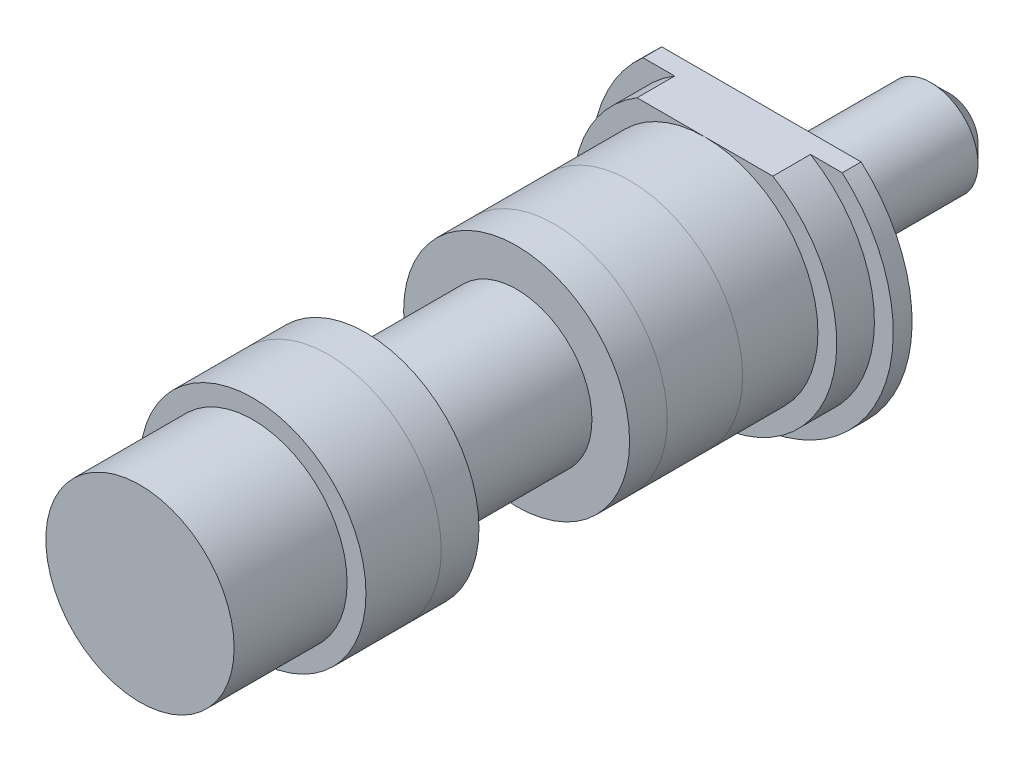
SolidWorks part; units mm, degrees
material "Stainless Steel (ferritic)"
ref_plane "Front" through (0, 0, 0) normal (0, 0, 1) x (1, 0, 0)
ref_plane "Top" through (0, 0, 0) normal (0, 1, 0) x (1, 0, 0)
ref_plane "Right" through (0, 0, 0) normal (1, 0, 0) x (0, 0, -1)
sketch "Sketch1" plane through (0, 0, 0) normal (0, 0, 1) x (1, 0, 0)
  circle A0 centre (0, 0) radius 4
  dimension "D1" = 8
extrude "Boss-Extrude1" add sketch "Sketch1" along normal blind 0.5
sketch "Sketch2" plane through (0, 0, 0.5) normal (0, 0, 1) x (1, 0, 0)
  circle A0 centre (0, 0) radius 3.5
extrude "Boss-Extrude2" add sketch "Sketch2" along normal blind 1
sketch "Sketch3" plane through (0, 0, 1.5) normal (0, 0, 1) x (1, 0, 0)
  circle A0 centre (0, 0) radius 3
extrude "Boss-Extrude3" add sketch "Sketch3" along normal blind 2
sketch "Sketch4" plane through (0, 0, 3.5) normal (0, 0, 1) x (1, 0, 0)
  circle A0 centre (0, 0) radius 2
extrude "Boss-Extrude4" add sketch "Sketch4" along normal blind 2
sketch "Sketch5" plane through (0, 0, 5.5) normal (0, 0, 1) x (1, 0, 0)
  circle A0 centre (0, 0) radius 3
extrude "Boss-Extrude5" add sketch "Sketch5" along normal blind 1
sketch "Sketch6" plane through (0, 0, 6.5) normal (0, 0, 1) x (1, 0, 0)
  circle A0 centre (0, 0) radius 2
extrude "Boss-Extrude6" add sketch "Sketch6" along normal blind 4
sketch "Sketch7" plane through (0, 0, 10.5) normal (0, 0, 1) x (1, 0, 0)
  circle A0 centre (0, 0) radius 3
extrude "Boss-Extrude7" add sketch "Sketch7" along normal blind 1
sketch "Sketch8" plane through (0, 0, 11.5) normal (0, 0, 1) x (1, 0, 0)
  circle A0 centre (0, 0) radius 2
extrude "Boss-Extrude8" add sketch "Sketch8" along normal blind 2
sketch "Sketch9" plane through (0, 0, 13.5) normal (0, 0, 1) x (1, 0, 0)
  circle A0 centre (0, 0) radius 2.5
extrude "Boss-Extrude9" add sketch "Sketch9" along normal blind 3
cosmetic thread "Cosmetic Thread1" parameters "D1"=3, "D2"=3.22
sketch "Sketch10" plane through (0, 0, 0) normal (0, 0, -1) x (-1, 0, 0)
  circle A0 centre (0, 0) radius 1.25
extrude "Boss-Extrude10" add sketch "Sketch10" along normal blind 5
chamfer "Chamfer1" distance 1 angle 45 1 edges at (-1.25, 0, 0)
chamfer "Chamfer2" distance 0.5 angle 45 1 edges at (-1.25, 0, -5)
sketch "Sketch11" plane through (0, 0, 1.5) normal (0, 0, 1) x (1, 0, 0)
  line L1 (-3.0382, 4) -> (3.0382, 4)
  line L2 (-3.0382, 4) -> (-3.0382, 3)
  line L3 (-3.0382, 3) -> (3.0382, 3)
  line L4 (3.0382, 4) -> (3.0382, 3)
  line L5 (-3.0382, 4) -> (3.0382, 3) construction
  line L6 (-3.0382, 3) -> (3.0382, 4) construction
  circle A0 centre (0, 0) radius 3.5 construction
  circle A1 centre (0, 0) radius 3.5 construction
  circle A2 centre (0, 0) radius 3 construction
  point P0 (0, 3.5)
extrude "Cut-Extrude1" cut sketch "Sketch11" against normal blind 6
ref_plane "Plane1" through (-2, 0, 0) normal (1, 0, 0) x (0, 0, -1)
sketch "Sketch12" plane through (-2, 0, 0) normal (1, 0, 0) x (0, 0, -1)
  line L0 (-6.5, 2) -> (-6.5, -2) construction
  circle A0 centre (-8.5, 0) radius 0.5
  dimension "D1" = 2
extrude "Cut-Extrude2" cut sketch "Sketch12" along normal blind 2
sketch "Sketch13" plane through (0, 0, -5) normal (0, 0, -1) x (-1, 0, 0)
  circle A0 centre (0, 0) radius 0.5
extrude "Cut-Extrude3" cut sketch "Sketch13" against normal blind 15
ref_plane "Plane2" through (0, 0, 0) normal (1, 0, 0) x (0, 0, -1)
sketch "Sketch17" plane through (0, 0, 0) normal (1, 0, 0) x (0, 0, -1)
  line L0 (-3.5, 3) -> (-3.5, -3) construction
  line L1 (-3.5, 2) -> (-5.5, 2)
  line L2 (-3.5, 2) -> (-3.5, 3)
  line L3 (-3.5, 3) -> (-5.5, 3)
  line L4 (-5.5, 2) -> (-5.5, 3)
  line L5 (-4.5, 3) -> (-4.5, 2) construction
  line L6 (-3.5, 2.5) -> (-5.5, 2.5) construction
  line L7 (-3.5, 2) -> (-5.5, 2) construction
  line L8 (-5.5, -3) -> (-5.5, 3) construction
  line L9 (2.3117, 0) -> (-11.5068, 0) construction
  point P224 (-4.5, 2.5)
revolve "Revolve1" add sketch "Sketch17" angle 360 about L9
sketch "Sketch18" plane through (0, 0, 0) normal (1, 0, 0) x (0, 0, -1)
  line L0 (0.7973, 0) -> (-16.4746, 0) construction
  line L1 (-11.5, 2) -> (-13.5, 2)
  line L2 (-11.5, 2) -> (-11.5, 3)
  line L3 (-11.5, 3) -> (-13.5, 3)
  line L4 (-13.5, 2) -> (-13.5, 3)
  line L5 (-12.5, 3) -> (-12.5, 2) construction
  line L6 (-11.5, 2.5) -> (-13.5, 2.5) construction
  point P192 (-12.5, 2.5)
  dimension "D1" = 2
  dimension "D2" = 1
revolve "Revolve2" add sketch "Sketch18" angle 360 about L0
